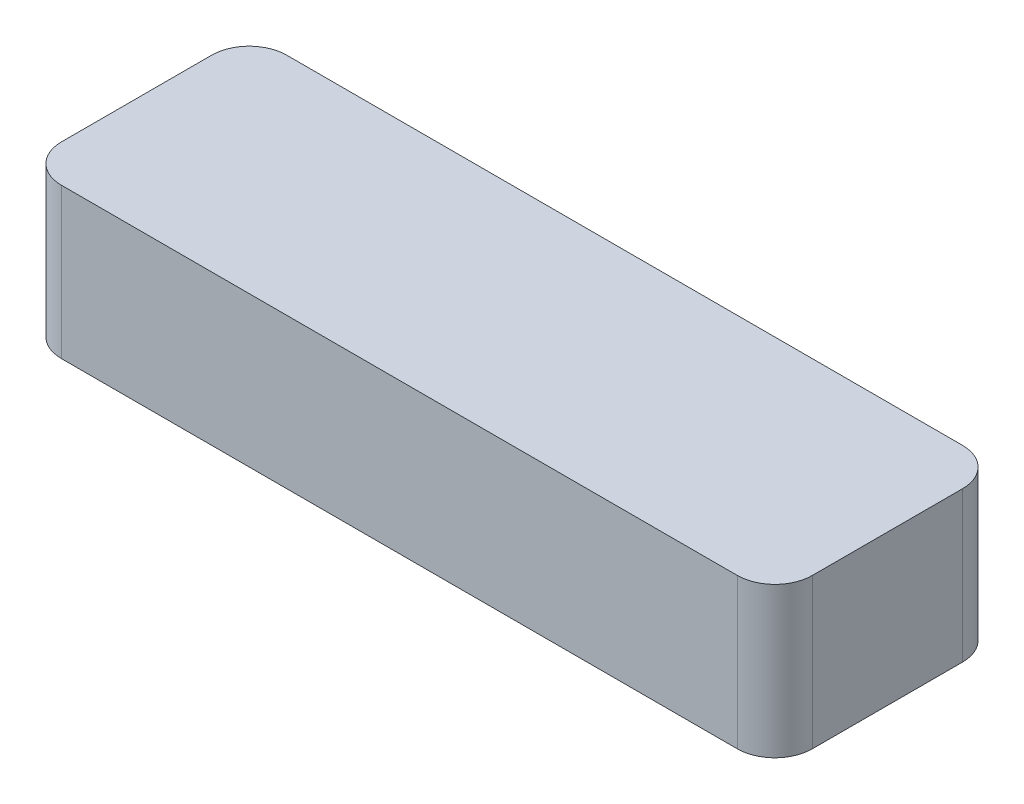
SolidWorks part; units mm, degrees
ref_plane "Front Plane" through (0, 0, 0) normal (0, 0, 1) x (1, 0, 0)
ref_plane "Top Plane" through (0, 0, 0) normal (0, 1, 0) x (1, 0, 0)
ref_plane "Right Plane" through (0, 0, 0) normal (1, 0, 0) x (0, 0, -1)
sketch "Sketch1" plane through (0, 0, 0) normal (0, 1, 0) x (1, 0, 0)
  line L1 (-4.5, 1.5) -> (4.5, 1.5)
  line L2 (-5, 1) -> (-5, -1)
  line L3 (-4.5, -1.5) -> (4.5, -1.5)
  line L4 (5, 1) -> (5, -1)
  arc A0 (-5, 1) -> (-4.5, 1.5) centre (-4.5, 1) cw
  arc A1 (-5, -1) -> (-4.5, -1.5) centre (-4.5, -1) ccw
  arc A2 (5, -1) -> (4.5, -1.5) centre (4.5, -1) cw
  arc A3 (5, 1) -> (4.5, 1.5) centre (4.5, 1) ccw
  point P0 (0, 0)
extrude "Boss-Extrude2" add sketch "Sketch1" along normal blind 2
